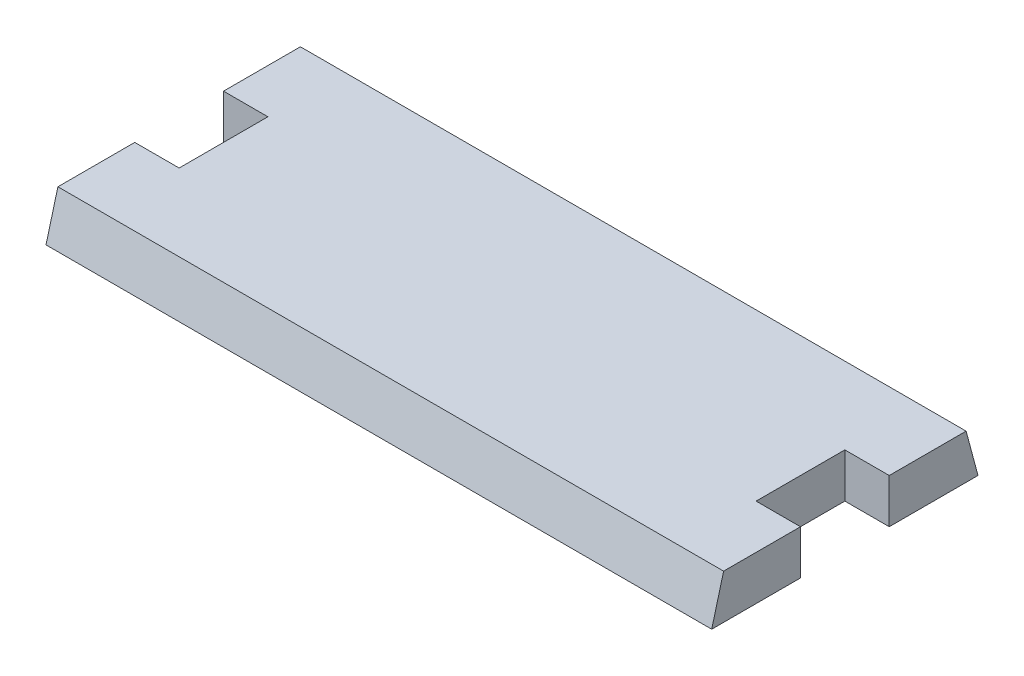
SolidWorks part; units mm, degrees
ref_plane "Front Plane" through (0, 0, 0) normal (0, 0, 1) x (1, 0, 0)
ref_plane "Top Plane" through (0, 0, 0) normal (0, 1, 0) x (1, 0, 0)
ref_plane "Right Plane" through (0, 0, 0) normal (1, 0, 0) x (0, 0, -1)
sketch "Sketch1" plane through (0, 0, 0) normal (0, 1, 0) x (1, 0, 0)
  line L0 (0, 0) -> (0, 20)
  line L1 (0, 20) -> (-10, 20)
  line L2 (-10, 20) -> (-10, 40)
  line L3 (-10, 40) -> (0, 40)
  line L4 (0, 40) -> (0, 60)
  line L5 (0, 60) -> (-150, 60)
  line L6 (-150, 60) -> (-150, 40)
  line L7 (-150, 40) -> (-140, 40)
  line L8 (-140, 40) -> (-140, 20)
  line L9 (-140, 20) -> (-150, 20)
  line L10 (-150, 20) -> (-150, 0)
  line L11 (-150, 0) -> (0, 0)
  dimension "D1" = 150
  dimension "D2" = 20
  dimension "D3" = 60
  dimension "D4" = 10
  dimension "D5" = 10
  dimension "D6" = 20
  dimension "D7" = 20
  dimension "D8" = 20
extrude "Boss-Extrude1" add sketch "Sketch1" along normal blind 10 contours L11 L0 L1 L2 L3 L4 L5 L6 L7 L8 L9 L10
draft "Draft21" type of draft neutral plane draft angle 15 faces to draft 1 face at (-75, 5, 0) neutral plane through (0, 0, 0) neutral plane normal (0, -1, 0) reverse direction yes parameters "D1"=15
draft "Draft22" type of draft neutral plane draft angle 15 faces to draft 1 face at (-75, 5, -60) neutral plane through (0, 0, 0) neutral plane normal (0, -1, 0) reverse direction yes parameters "D1"=15
